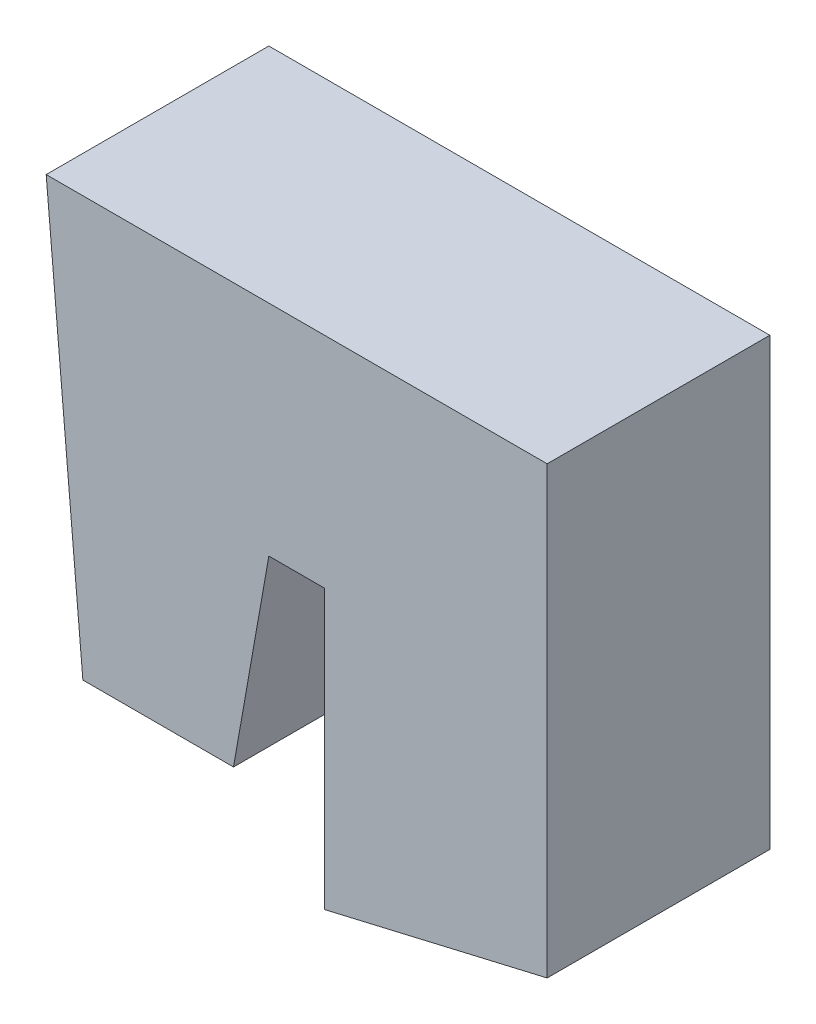
SolidWorks part; units mm, degrees
material "1060 Alloy"
ref_plane "Front Plane" through (0, 0, 0) normal (0, 0, 1) x (1, 0, 0)
ref_plane "Top Plane" through (0, 0, 0) normal (0, 1, 0) x (1, 0, 0)
ref_plane "Right Plane" through (0, 0, 0) normal (1, 0, 0) x (0, 0, -1)
sketch "Sketch1" plane through (0, 0, 0) normal (0, 0, 1) x (1, 0, 0)
  line L0 (2.5, -22.3377) -> (22.5, -17.6623)
  line L1 (22.5, -17.6623) -> (22.5, 22.3377)
  line L2 (2.5, -22.3377) -> (2.5, 2.6623)
  line L3 (22.5, 22.3377) -> (-22.5, 22.3377)
  line L4 (-22.5, 22.3377) -> (-19.2038, -15.3377)
  line L5 (2.5, 2.6623) -> (-2.5, 2.6623)
  line L6 (-2.5, 2.6623) -> (-5.6739, -15.3377)
  line L7 (-5.6739, -15.3377) -> (-19.2038, -15.3377)
  dimension "D1" = 85
  dimension "D2" = 100
  dimension "D3" = 45
  dimension "D4" = 40
  dimension "D5" = 5
  dimension "D6" = 25
extrude "Boss-Extrude1" add sketch "Sketch1" against normal blind 20
